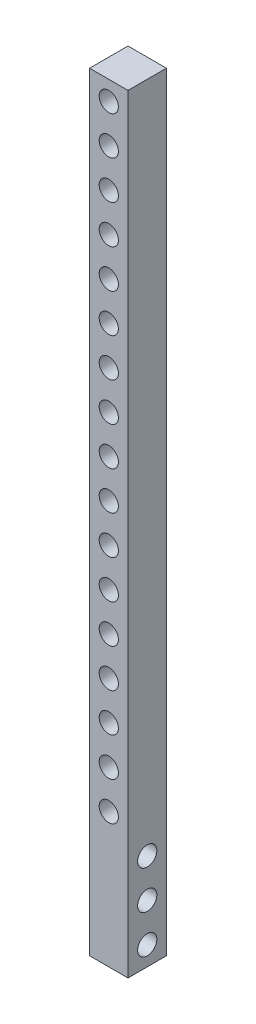
SolidWorks part; units mm, degrees
ref_plane "Plan de face" through (0, 0, 0) normal (0, 0, 1) x (1, 0, 0)
ref_plane "Plan de dessus" through (0, 0, 0) normal (0, 1, 0) x (1, 0, 0)
ref_plane "Plan de droite" through (0, 0, 0) normal (1, 0, 0) x (0, 0, -1)
sketch "Esquisse1" plane through (0, 0, 0) normal (0, 0, 1) x (1, 0, 0)
  line L0 (0, 100) -> (0, 92.8586) construction
  line L1 (5, 100) -> (-5, 100)
  line L2 (5, 100) -> (5, -100)
  line L3 (5, -100) -> (-5, -100)
  line L4 (-5, 100) -> (-5, -100)
  line L5 (5, 100) -> (-5, -100) construction
  line L6 (5, -100) -> (-5, 100) construction
  circle A0 centre (0, 95) radius 2.5
  circle A1 centre (0, 85) radius 2.5
  circle A2 centre (0, 75) radius 2.5
  circle A3 centre (0, 65) radius 2.5
  circle A4 centre (0, 55) radius 2.5
  circle A5 centre (0, 45) radius 2.5
  circle A6 centre (0, 35) radius 2.5
  circle A7 centre (0, 25) radius 2.5
  circle A8 centre (0, 15) radius 2.5
  circle A9 centre (0, 5) radius 2.5
  circle A10 centre (0, -5) radius 2.5
  circle A11 centre (0, -15) radius 2.5
  circle A12 centre (0, -25) radius 2.5
  circle A13 centre (0, -35) radius 2.5
  circle A14 centre (0, -45) radius 2.5
  circle A15 centre (0, -55) radius 2.5
  circle A16 centre (0, -65) radius 2.5
  point P0 (0, 0)
  dimension "D4" = 5
  dimension "D1" = 200
  dimension "D2" = 10
  dimension "D3" = 5
  dimension "D5" = 17
extrude "BASE" add sketch "Esquisse1" along normal blind 10
sketch "Esquisse4" plane through (-5, 0, 0) normal (-1, 0, 0) x (0, 0, 1)
  line L0 (5, -100) -> (5, -65.1003) construction
  line L1 (10, -100) -> (0, -100) construction
  circle A0 centre (5, -95) radius 2.5
  circle A1 centre (5, -85) radius 2.5
  circle A2 centre (5, -75) radius 2.5
  dimension "D2" = 5
  dimension "D3" = 5
  dimension "D4" = 5
  dimension "D1" = 5
  dimension "D5" = 10
  dimension "D6" = 10
extrude "Enlèv. mat.-Extru.2" cut sketch "Esquisse4" against normal through all
